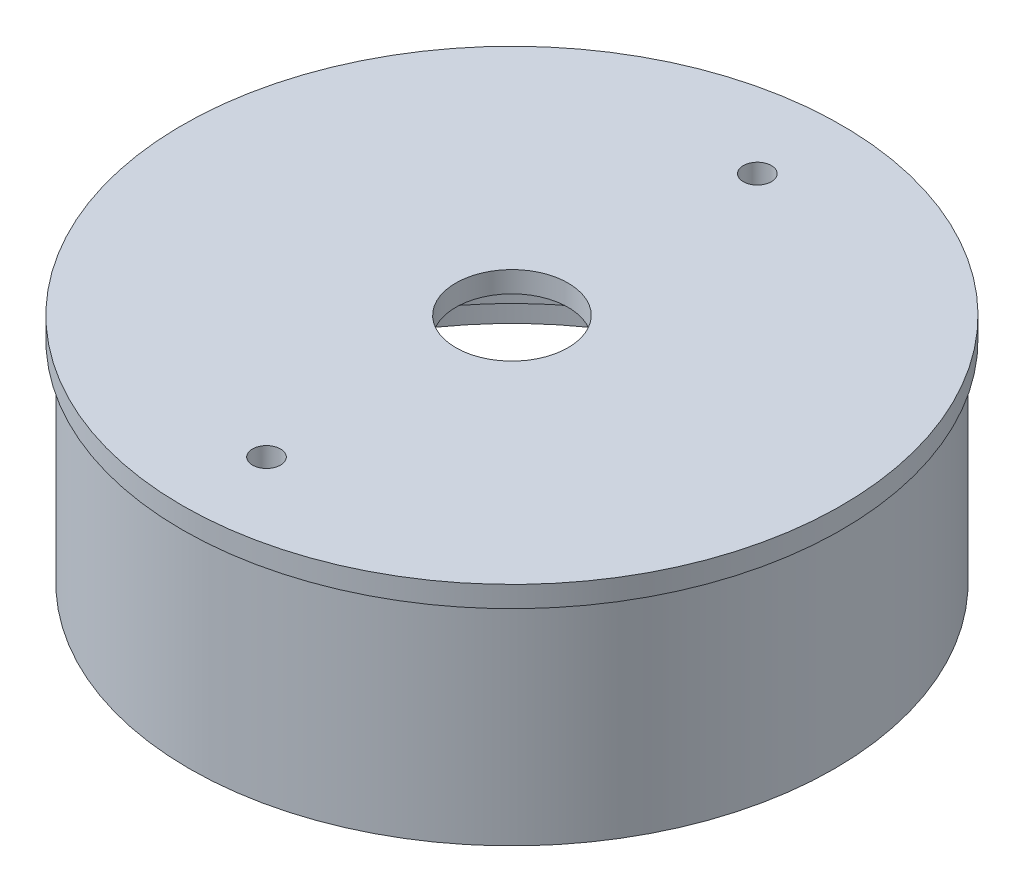
SolidWorks part; units mm, degrees
ref_plane "Front Plane" through (0, 0, 0) normal (0, 0, 1) x (1, 0, 0)
ref_plane "Top Plane" through (0, 0, 0) normal (0, 1, 0) x (1, 0, 0)
ref_plane "Right Plane" through (0, 0, 0) normal (1, 0, 0) x (0, 0, -1)
sketch "Sketch1" plane through (0, 0, 0) normal (0, 1, 0) x (1, 0, 0)
  circle A0 centre (0, 0) radius 45.25
  circle A1 centre (0, 0) radius 46
  dimension "D1" = 90.5
  dimension "D2" = 92
extrude "Boss-Extrude1" add sketch "Sketch1" along normal blind 30
sketch "Sketch3" plane through (0, 30, 0) normal (0, 1, 0) x (1, 0, 0)
  circle A0 centre (0, 0) radius 47
extrude "Boss-Extrude2" add sketch "Sketch3" along normal blind 3
sketch "Sketch4" plane through (0, 33, 0) normal (0, 1, 0) x (1, 0, 0)
  line L0 (0, 0) -> (0, 35) construction
  line L1 (0, 0) -> (25.5047, 0) construction
  circle A0 centre (0, 35) radius 2
  circle A1 centre (0, -35) radius 2
  circle A2 centre (0, 0) radius 8
  dimension "D2" = 4
  dimension "D3" = 16
  dimension "D1" = 35
extrude "Cut-Extrude1" cut sketch "Sketch4" against normal through all
sketch "Sketch5" plane through (0, 30, 0) normal (0, -1, 0) x (1, 0, 0)
  circle A0 centre (0, 0) radius 44.5
  circle A2 centre (0, 0) radius 45.25 construction
  circle A3 centre (0, 0) radius 45.25
  dimension "D1" = 89
extrude "Boss-Extrude3" add sketch "Sketch5" along normal blind 27
